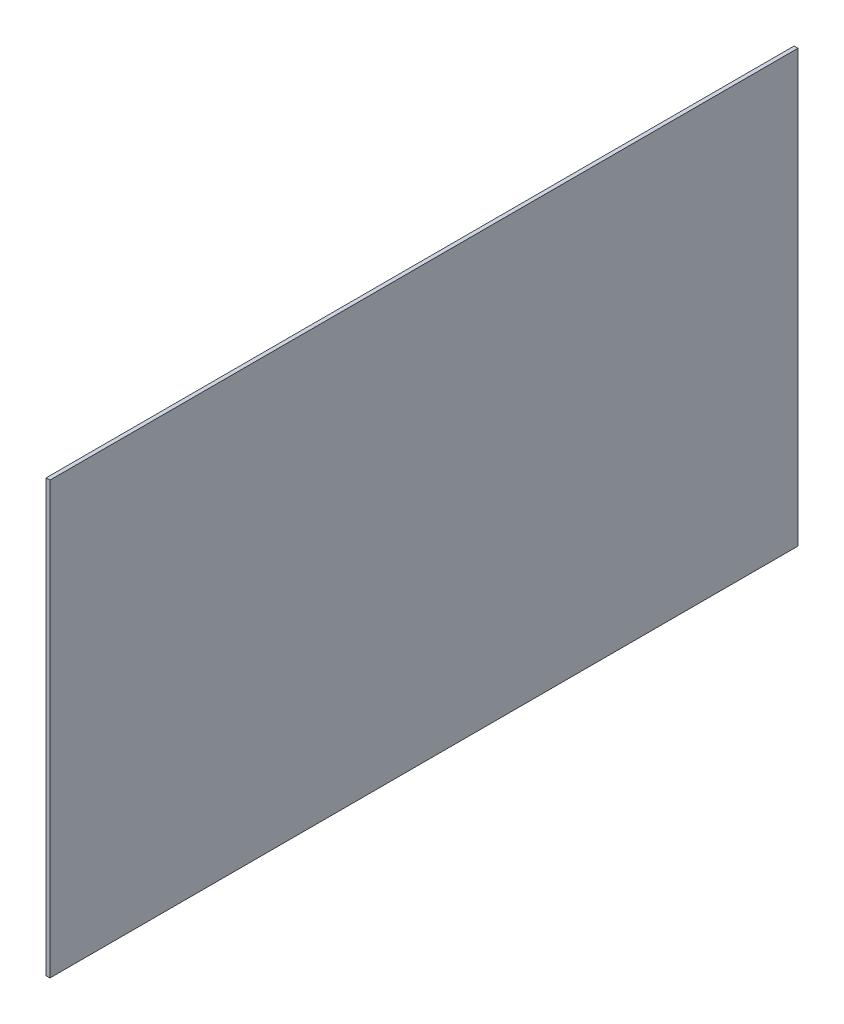
SolidWorks part; units mm, degrees
material "Acrylic (Medium-high impact)"
ref_plane "Front Plane" through (0, 0, 0) normal (0, 0, 1) x (1, 0, 0)
ref_plane "Top Plane" through (0, 0, 0) normal (0, 1, 0) x (1, 0, 0)
ref_plane "Right Plane" through (0, 0, 0) normal (1, 0, 0) x (0, 0, -1)
sketch "Sketch1" plane through (0, 0, 0) normal (1, 0, 0) x (0, 0, -1)
  line L1 (0, 0) -> (1828.8, 0)
  line L2 (0, 0) -> (0, 1054.1)
  line L3 (0, 1054.1) -> (1828.8, 1054.1)
  line L4 (1828.8, 0) -> (1828.8, 1054.1)
  dimension "D1" = 1054.1
  dimension "D2" = 1828.8
extrude "Boss-Extrude1" add sketch "Sketch1" along normal blind 9.525
